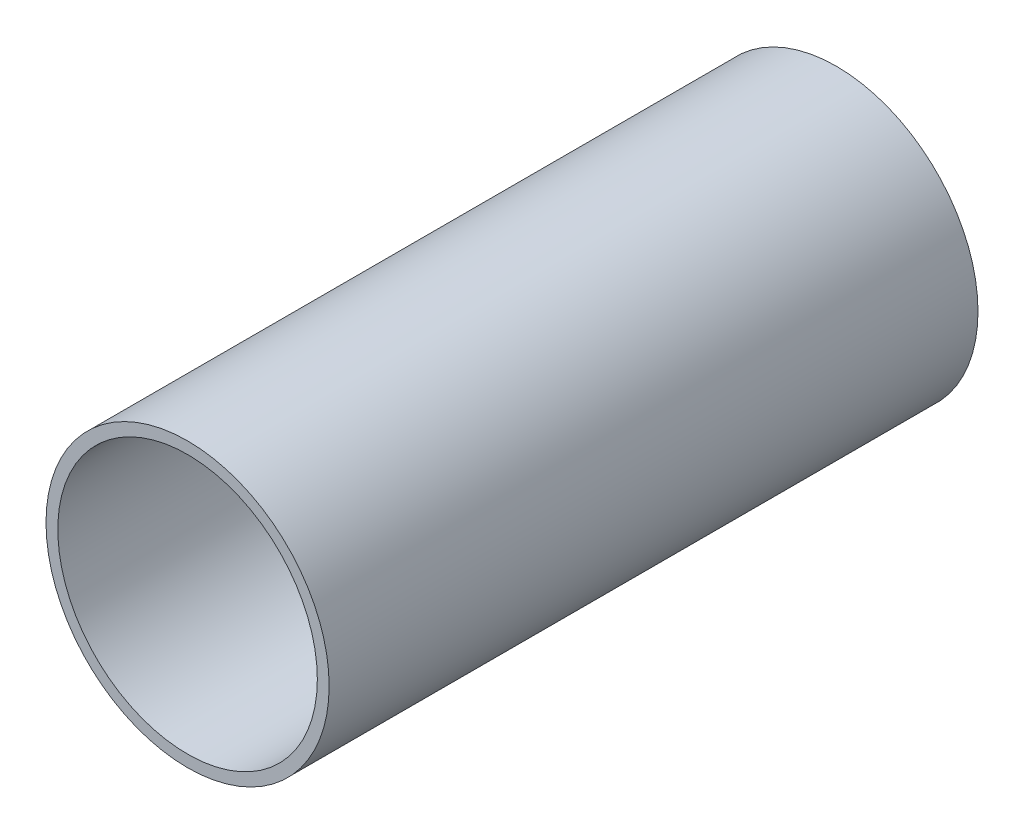
SolidWorks part; units mm, degrees
ref_plane "Front Plane" through (0, 0, 0) normal (0, 0, 1) x (1, 0, 0)
ref_plane "Top Plane" through (0, 0, 0) normal (0, 1, 0) x (1, 0, 0)
ref_plane "Right Plane" through (0, 0, 0) normal (1, 0, 0) x (0, 0, -1)
sketch "Sketch1" plane through (0, 0, 0) normal (0, 0, 1) x (1, 0, 0)
  circle A0 centre (0, 0) radius 38.1
  circle A1 centre (0, 0) radius 34.925
  dimension "D1" = 3.175
extrude "Boss-Extrude1" add sketch "Sketch1" along normal blind 174.625
